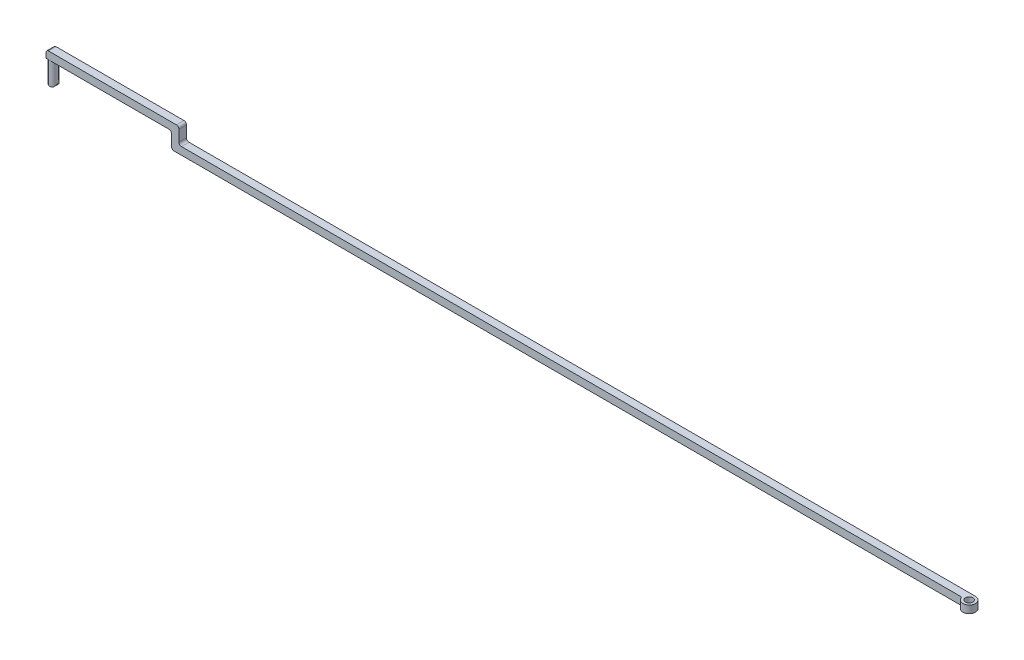
SolidWorks part; units mm, degrees
ref_plane "Piano frontale" through (0, 0, 0) normal (0, 0, 1) x (1, 0, 0)
ref_plane "Piano superiore" through (0, 0, 0) normal (0, 1, 0) x (1, 0, 0)
ref_plane "Piano destro" through (0, 0, 0) normal (1, 0, 0) x (0, 0, -1)
sketch "Schizzo1" plane through (0, 0, 0) normal (0, 0, 1) x (1, 0, 0)
  line L1 (0, 0) -> (-185, 0)
  line L2 (0, 0) -> (0, 6)
  line L3 (0, 6) -> (-185, 6)
  line L4 (-185, 0) -> (-185, 6)
  dimension "D1" = 185
  dimension "D2" = 6
extrude "Estrusione-Estrusione1" add sketch "Schizzo1" along normal blind 1.5
sketch "Schizzo2" plane through (0, 0, 1.5) normal (0, 0, 1) x (1, 0, 0)
  line L1 (-184.5, 0) -> (-184, 0)
  line L2 (-185, 0.5) -> (-185, 5.5)
  line L4 (-183.5, 0.5) -> (-183.5, 4)
  line L6 (-184.5, 6) -> (-159, 6)
  line L8 (-183, 4.5) -> (-160.5, 4.5)
  line L12 (-158.5, 5.5) -> (-158.5, 3.25)
  line L13 (0, 0) -> (0, 6) construction
  line L14 (-159.5, 1.25) -> (0, 1.25)
  line L15 (-160, 1.75) -> (-160, 4)
  line L16 (-158, 2.75) -> (0, 2.75)
  line L17 (0, 1.25) -> (0, 2.75)
  arc A0 (-184, 0) -> (-183.5, 0.5) centre (-184, 0.5) ccw
  arc A1 (-184.5, 0) -> (-185, 0.5) centre (-184.5, 0.5) cw
  arc A2 (-158, 2.75) -> (-158.5, 3.25) centre (-158, 3.25) cw
  arc A3 (-159.5, 1.25) -> (-160, 1.75) centre (-159.5, 1.75) cw
  arc A4 (-159, 6) -> (-158.5, 5.5) centre (-159, 5.5) cw
  arc A5 (-160, 4) -> (-160.5, 4.5) centre (-160.5, 4) ccw
  arc A6 (-184.5, 6) -> (-185, 5.5) centre (-184.5, 5.5) ccw
  arc A7 (-183.5, 4) -> (-183, 4.5) centre (-183, 4) cw
  point P12 (-185, 0)
  point P21 (-158.5, 2.75)
  point P26 (-158.5, 6)
  point P29 (-160, 4.5)
  point P32 (-185, 6)
  dimension "D4" = 0.5
  dimension "D1" = 1.5
  dimension "D2" = 1.5
  dimension "D3" = 1.5
  dimension "D5" = 25
  dimension "D6" = 1.5
  dimension "D7" = 3.25
extrude "Taglio-Estrusione1" cut sketch "Schizzo2" against normal blind 1.5 flip side to cut
sketch "Schizzo5" plane through (0, 0, 0) normal (0, -1, 0) x (1, 0, 0)
  line L0 (-185, 0) -> (-185, 1.5) construction
  line L1 (-185, 0) -> (-184.5, 0) construction
  line L3 (-185.1668, 1.6081) -> (-182.8724, 1.6081)
  line L4 (-185.1668, 1.6081) -> (-185.1668, -0.2197)
  line L5 (-185.1668, -0.2197) -> (-182.8724, -0.2197)
  line L6 (-182.8724, 1.6081) -> (-182.8724, -0.2197)
  circle A0 centre (-184.25, 0.75) radius 0.75
  dimension "D1" = 1.5
  dimension "D2" = 0.75
  dimension "D3" = 0.75
  dimension "D4" = 2.2945
  dimension "D5" = 1.8277
  dimension "D6" = 0.8581
  dimension "D7" = 0.9168
extrude "Taglio-Estrusione3" cut sketch "Schizzo5" against normal up to surface (4.5 mm away) up to face at (-171.75, 4.5, 0.75)
sketch "Schizzo6" plane through (0, 2.75, 0) normal (0, 1, 0) x (1, 0, 0)
  line L0 (0, 0) -> (-158, 0) construction
  circle A0 centre (-1.2247, -1.25) radius 1.25
  dimension "D1" = 2.5
extrude "Estrusione-Estrusione3" add sketch "Schizzo6" against normal up to surface (1.5 mm away) up to face at (-79.75, 1.25, 0.75)
sketch "Schizzo7" plane through (0, 2.75, 0) normal (0, 1, 0) x (1, 0, 0)
  line L0 (-1.2247, 0) -> (-1.2247, 0.5343)
  line L1 (-1.2247, 0.5343) -> (0.7257, 0.5343)
  line L2 (0.7257, 0.5343) -> (0.7257, -1.25)
  line L3 (0.7257, -1.25) -> (0.0253, -1.25)
  circle A0 centre (-1.2247, -1.25) radius 0.75
  arc A1 (0.0253, -1.25) -> (-1.2247, 0) centre (-1.2247, -1.25) ccw
  dimension "D1" = 1.5
  dimension "D2" = 1.25
  dimension "D3" = 1.9505
  dimension "D4" = 1.7843
extrude "Taglio-Estrusione4" cut sketch "Schizzo7" against normal up to surface (1.5 mm away) up to face at (-64.2399, 1.25, 1.0449)
